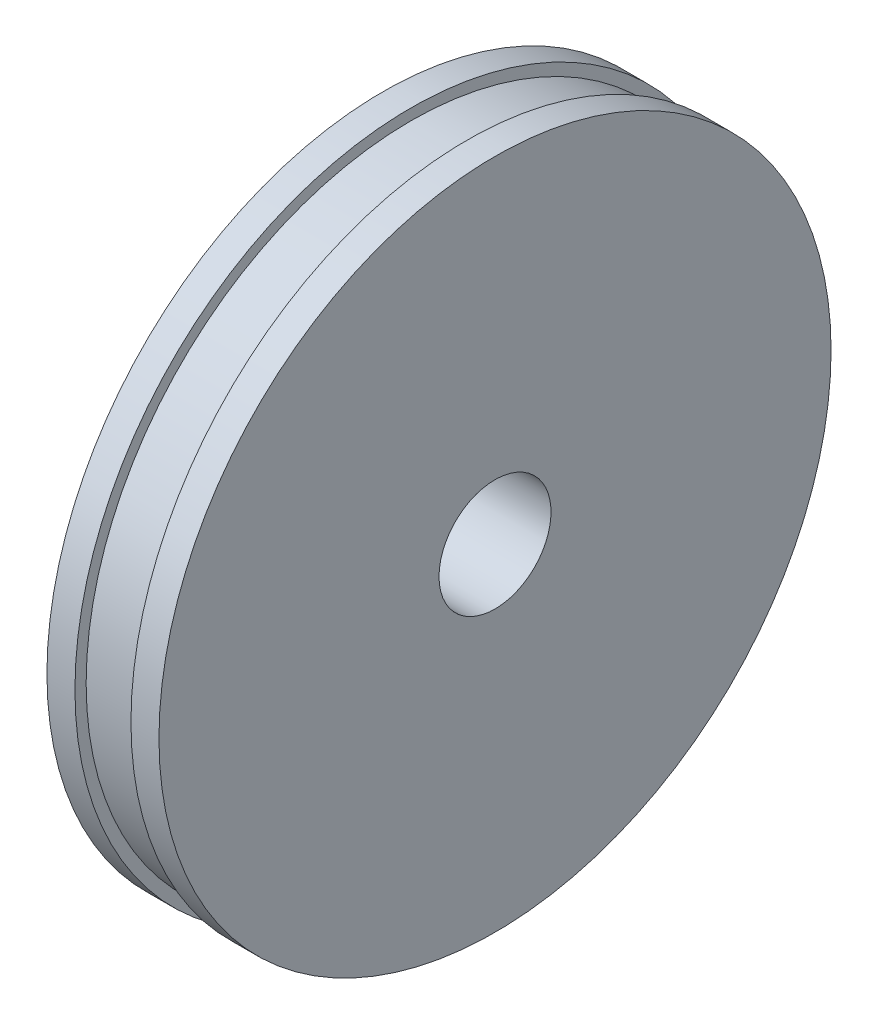
SolidWorks part; units mm, degrees
ref_plane "Front Plane" through (0, 0, 0) normal (0, 0, 1) x (1, 0, 0)
ref_plane "Top Plane" through (0, 0, 0) normal (0, 1, 0) x (1, 0, 0)
ref_plane "Right Plane" through (0, 0, 0) normal (1, 0, 0) x (0, 0, -1)
sketch "Sketch1" plane through (0, 0, 0) normal (0, 0, 1) x (1, 0, 0)
  line L0 (0, 0) -> (0, 300)
  line L1 (0, 300) -> (25, 300)
  line L2 (25, 300) -> (25, 290)
  line L3 (25, 290) -> (75, 290)
  line L4 (75, 290) -> (75, 300)
  line L5 (75, 300) -> (100, 300)
  line L6 (100, 300) -> (100, 0)
  line L7 (0, 0) -> (100, 0)
  dimension "D1" = 300
  dimension "D2" = 100
  dimension "D3" = 50
  dimension "D4" = 25
  dimension "D5" = 10
revolve "Revolve1" add sketch "Sketch1" angle 360 about L7
sketch "Sketch2" plane through (0, 0, 0) normal (-1, 0, 0) x (0, 0, 1)
  circle A0 centre (0, 0) radius 50
extrude "Cut-Extrude1" cut sketch "Sketch2" against normal through all
